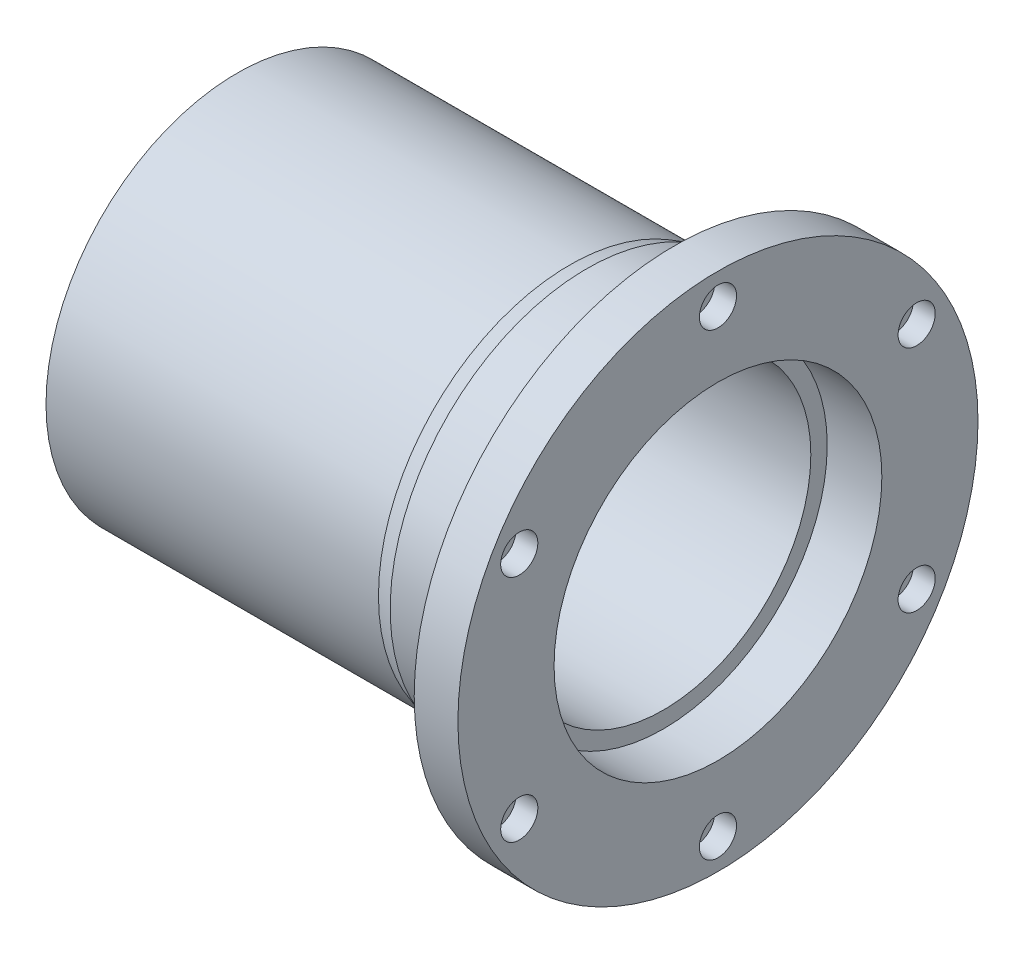
SolidWorks part; units mm, degrees
ref_plane "Piano frontale" through (0, 0, 0) normal (0, 0, 1) x (1, 0, 0)
ref_plane "Piano superiore" through (0, 0, 0) normal (0, 1, 0) x (1, 0, 0)
ref_plane "Piano destro" through (0, 0, 0) normal (1, 0, 0) x (0, 0, -1)
sketch "Schizzo1" plane through (0, 0, 0) normal (0, 0, 1) x (1, 0, 0)
  line L0 (0, 0) -> (-46.6241, 0)
  line L1 (-108.2133, 75) -> (-108.2133, 87.5)
  line L2 (-108.2133, 87.5) -> (43.9264, 87.5)
  line L3 (43.9264, 87.5) -> (51.7867, 90)
  line L4 (51.7867, 90) -> (91.7867, 90)
  line L5 (91.7867, 90) -> (91.7867, 119)
  line L6 (91.7867, 119) -> (111.7867, 119)
  line L7 (111.7867, 119) -> (111.7867, 75)
  line L8 (111.7867, 75) -> (86.7867, 75)
  line L9 (86.7867, 75) -> (86.7867, 67.5)
  line L10 (86.7867, 67.5) -> (-83.2133, 67.5)
  line L11 (-83.2133, 67.5) -> (-83.2133, 75)
  line L12 (-83.2133, 75) -> (-108.2133, 75)
  dimension "D1" = 87.5
  dimension "D2" = 75
  dimension "D3" = 67.5
  dimension "D4" = 75
  dimension "D5" = 119
  dimension "D6" = 220
  dimension "D7" = 25
  dimension "D8" = 25
  dimension "D9" = 90
  dimension "D10" = 40
  dimension "D11" = 20
revolve "Rivoluzione1" add sketch "Schizzo1" angle 360 about L0
sketch "Schizzo12" plane through (111.7867, 0, 0) normal (1, 0, 0) x (0, 0, -1)
  circle A0 centre (0, -105) radius 5
  dimension "D1" = 105
  dimension "D2" = 0
extrude "Taglio-Estrusione1" cut sketch "Schizzo12" against normal up to surface (20 mm away) up to face at (91.7867, 0, -119)
sketch "Schizzo13" plane through (111.7867, 0, 0) normal (1, 0, 0) x (0, 0, -1)
  circle A0 centre (0, -105) radius 8.5
extrude "Taglio-Estrusione2" cut sketch "Schizzo13" against normal blind 10
pattern_circular "RipetizioneCircolare1" count 6 over 360 about axis through (0, 0, 0) along (1, 0, 0) of "Taglio-Estrusione1", "Taglio-Estrusione2"
